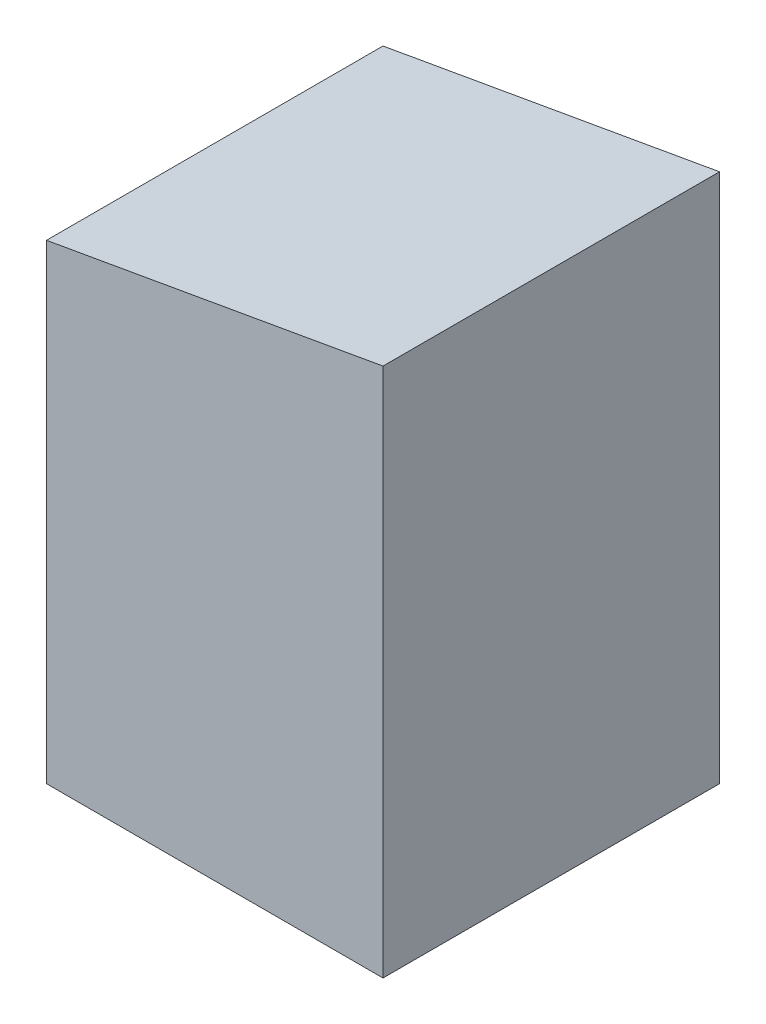
SolidWorks part; units mm, degrees
ref_plane "Front Plane" through (0, 0, 0) normal (0, 0, 1) x (1, 0, 0)
ref_plane "Top Plane" through (0, 0, 0) normal (0, 1, 0) x (1, 0, 0)
ref_plane "Right Plane" through (0, 0, 0) normal (1, 0, 0) x (0, 0, -1)
sketch "Sketch1" plane through (0, 0, 0) normal (0, 1, 0) x (1, 0, 0)
  line L1 (-44.45, -44.45) -> (44.45, -44.45)
  line L2 (-44.45, -44.45) -> (-44.45, 44.45)
  line L3 (-44.45, 44.45) -> (44.45, 44.45)
  line L4 (44.45, -44.45) -> (44.45, 44.45)
  line L5 (-44.45, -44.45) -> (44.45, 44.45) construction
  line L6 (-44.45, 44.45) -> (44.45, -44.45) construction
  point P0 (0, 0)
  dimension "D1" = 88.9
  dimension "D2" = 88.9
extrude "Boss-Extrude1" add sketch "Sketch1" along normal blind 140
sketch "Sketch2" plane through (0, 0, 44.45) normal (0, 0, 1) x (1, 0, 0)
  line L0 (44.45, 140) -> (-44.45, 124.3245)
  line L1 (-44.45, 140) -> (-44.45, 0) construction
  line L2 (-44.45, 124.3245) -> (-44.45, 140)
  line L3 (-44.45, 140) -> (44.45, 140)
  dimension "D1" = 10
extrude "Cut-Extrude1" cut sketch "Sketch2" against normal blind 135
